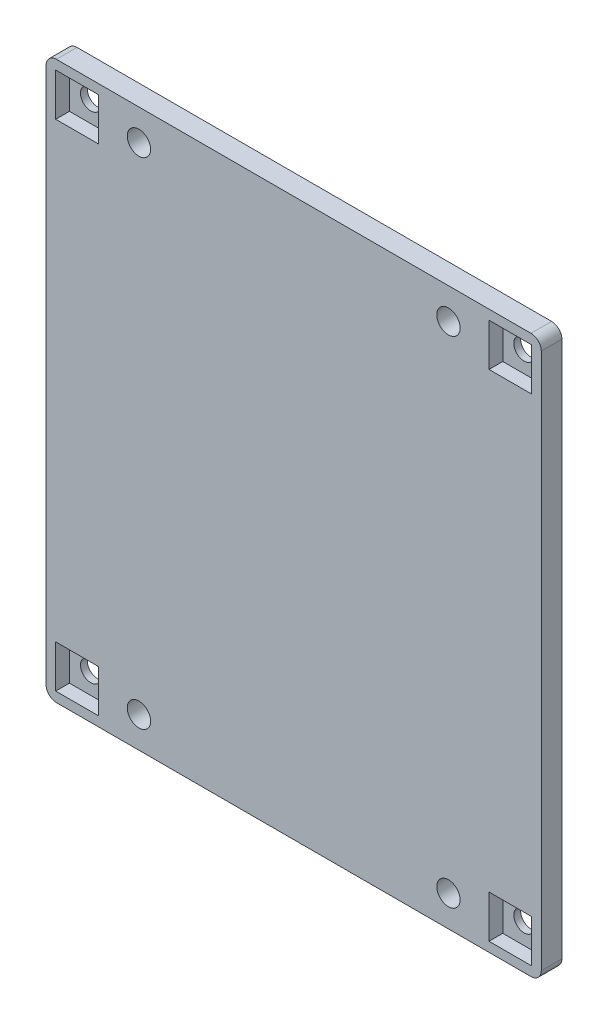
SolidWorks part; units mm, degrees
ref_plane "Alzado" through (0, 0, 0) normal (0, 0, 1) x (1, 0, 0)
ref_plane "Planta" through (0, 0, 0) normal (0, 1, 0) x (1, 0, 0)
ref_plane "Vista lateral" through (0, 0, 0) normal (1, 0, 0) x (0, 0, -1)
sketch "Model" plane through (0, 0, 0) normal (0, 0, 1) x (1, 0, 0)
  line L0 (6.1877, 221.4099) -> (6.1877, 299.4145)
  line L1 (7.6877, 300.9145) -> (76.6901, 300.9145)
  line L2 (78.1901, 299.4145) -> (78.1901, 221.4099)
  line L3 (76.6901, 219.9099) -> (7.6877, 219.9099)
  arc A0 (78.1901, 299.4145) -> (76.6901, 300.9145) centre (76.6901, 299.4145) ccw
  arc A1 (76.6901, 219.9099) -> (78.1901, 221.4099) centre (76.6901, 221.4099) ccw
  arc A2 (6.1877, 221.4099) -> (7.6877, 219.9099) centre (7.6877, 221.4099) ccw
  arc A3 (7.6877, 300.9145) -> (6.1877, 299.4145) centre (7.6877, 299.4145) ccw
  circle A4 centre (73.6901, 224.4096) radius 1.5
  circle A5 centre (10.6874, 296.4145) radius 1.5
  circle A6 centre (10.6874, 224.4096) radius 1.5
  circle A7 centre (73.6901, 296.4145) radius 1.5
  circle A8 centre (19.687, 296.4145) radius 1.7
  circle A9 centre (64.6904, 296.4145) radius 1.7
  circle A10 centre (19.687, 224.4096) radius 1.7
  circle A11 centre (64.6904, 224.4096) radius 1.7
extrude "Saliente-Extruir1" add sketch "Model" along normal blind 3
sketch "Croquis2" plane through (0, 0, 3) normal (0, 0, 1) x (1, 0, 0)
  line L1 (7.5874, 299.5145) -> (13.7874, 299.5145)
  line L2 (7.5874, 299.5145) -> (7.5874, 293.3145)
  line L3 (7.5874, 293.3145) -> (13.7874, 293.3145)
  line L4 (13.7874, 299.5145) -> (13.7874, 293.3145)
  line L5 (7.5874, 299.5145) -> (13.7874, 293.3145) construction
  line L6 (7.5874, 293.3145) -> (13.7874, 299.5145) construction
  line L7 (70.5901, 299.5145) -> (76.7901, 299.5145)
  line L8 (70.5901, 299.5145) -> (70.5901, 293.3145)
  line L9 (70.5901, 293.3145) -> (76.7901, 293.3145)
  line L10 (76.7901, 299.5145) -> (76.7901, 293.3145)
  line L11 (70.5901, 299.5145) -> (76.7901, 293.3145) construction
  line L12 (70.5901, 293.3145) -> (76.7901, 299.5145) construction
  line L13 (70.5901, 227.5096) -> (76.7901, 227.5096)
  line L14 (70.5901, 227.5096) -> (70.5901, 221.3096)
  line L15 (70.5901, 221.3096) -> (76.7901, 221.3096)
  line L16 (76.7901, 227.5096) -> (76.7901, 221.3096)
  line L17 (70.5901, 227.5096) -> (76.7901, 221.3096) construction
  line L18 (70.5901, 221.3096) -> (76.7901, 227.5096) construction
  line L19 (13.7874, 227.5096) -> (7.5874, 227.5096)
  line L20 (13.7874, 227.5096) -> (13.7874, 221.3096)
  line L21 (13.7874, 221.3096) -> (7.5874, 221.3096)
  line L22 (7.5874, 227.5096) -> (7.5874, 221.3096)
  line L23 (13.7874, 227.5096) -> (7.5874, 221.3096) construction
  line L24 (13.7874, 221.3096) -> (7.5874, 227.5096) construction
  point P0 (10.6874, 296.4145)
  point P5 (73.6901, 296.4145)
  point P12 (73.6901, 224.4096)
  point P19 (10.6874, 224.4096)
extrude "Cortar-Extruir1" cut sketch "Croquis2" against normal blind 2
